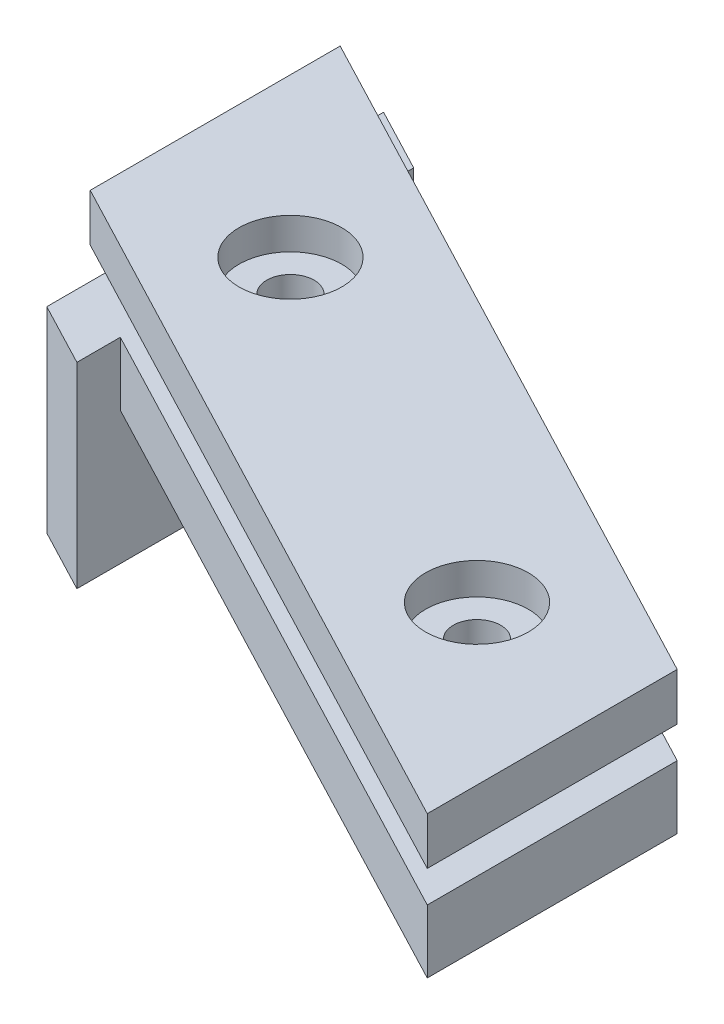
SolidWorks part; units mm, degrees
ref_plane "Front Plane" through (0, 0, 0) normal (0, 0, 1) x (1, 0, 0)
ref_plane "Top Plane" through (0, 0, 0) normal (0, 1, 0) x (1, 0, 0)
ref_plane "Right Plane" through (0, 0, 0) normal (1, 0, 0) x (0, 0, -1)
sketch "Sketch1" plane through (0, 0, 0) normal (0, 1, 0) x (1, 0, 0)
  line L0 (0, 6) -> (0, -19) construction
  line L1 (0, -19) -> (24.7992, -19) construction
  circle A0 centre (0, 0) radius 6
  circle A1 centre (24.7992, -13) radius 6
  dimension "D1" = 28
  dimension "D2" = 12
  dimension "D3" = 12
  dimension "D4" = 25
sketch "Sketch3" plane through (0, 0, 0) normal (0, 1, 0) x (1, 0, 0)
  line L0 (-10, 13.1456) -> (-10, -2.6614)
  line L1 (-10, -2.6614) -> (34.7992, -26.1456)
  line L2 (34.7992, -26.1456) -> (34.7992, -10.3386)
  line L3 (34.7992, -10.3386) -> (-10, 13.1456)
  line L5 (0, 0) -> (24.7992, -13) construction
  line L6 (0, 6) -> (0, -19) construction
  dimension "D1" = 7
  dimension "D2" = 7
  dimension "D3" = 10
  dimension "D4" = 10
extrude "Boss-Extrude1" add sketch "Sketch3" along normal blind 3
extrude "Boss-Extrude3" add sketch "Sketch1" against normal blind 2
sketch "Sketch4" plane through (0, 3, 0) normal (0, 1, 0) x (1, 0, 0)
  circle A0 centre (0, 0) radius 1.5
  circle A1 centre (24.7992, -13) radius 1.5
  dimension "D1" = 3
  dimension "D2" = 3
extrude "Cut-Extrude1" cut sketch "Sketch4" against normal through all
sketch "Sketch5" plane through (0, 3, 0) normal (0, 1, 0) x (1, 0, 0)
  circle A0 centre (0, 0) radius 3.25
  circle A1 centre (24.7992, -13) radius 3.25
  dimension "D1" = 6.5
  dimension "D2" = 6.5
extrude "Cut-Extrude2" cut sketch "Sketch5" against normal blind 2
sketch "Sketch6" plane through (0, -2, 0) normal (0, -1, 0) x (1, 0, 0)
  line L0 (-10, 2.6614) -> (-10, -13.1456)
  line L1 (-10, -13.1456) -> (34.7992, 10.3386)
  line L2 (34.7992, 10.3386) -> (34.7992, 26.1456)
  line L3 (34.7992, 26.1456) -> (-10, 2.6614)
  circle A0 centre (0, 0) radius 1.5
  circle A1 centre (24.7992, 13) radius 1.5
  circle A2 centre (24.7992, 13) radius 1.5 construction
  circle A3 centre (0, 0) radius 1.5 construction
extrude "Boss-Extrude4" add sketch "Sketch6" along normal blind 4 separate body
sketch "Sketch7" plane through (0, -2, 0) normal (0, 1, 0) x (1, 0, 0)
  line L2 (-8, 14.8437) -> (-8, 12.0972) construction
  line L4 (-8, 12.0972) -> (-8, -3.7098) construction
  line L6 (-10, 15.8921) -> (-10, -5.4079)
  line L7 (-10, -5.4079) -> (-6, -7.5047)
  line L8 (-6, -7.5047) -> (-6, 13.7953)
  line L9 (-6, 13.7953) -> (-10, 15.8921)
  line L10 (-10, 13.1456) -> (34.7992, -10.3386) construction
  line L11 (-10, -2.6614) -> (-10, 13.1456) construction
  line L12 (34.7992, -26.1456) -> (-10, -2.6614) construction
  line L13 (-8, -3.7098) -> (-8, -6.4563) construction
  dimension "D1" = 21.3
  dimension "D2" = 4
extrude "Boss-Extrude5" add sketch "Sketch7" against normal blind 12.4
sketch "Sketch9" [suppressed] plane through (0, -14.4, 0) normal (0, -1, 0) x (1, 0, 0)
  line L0 (-6, 5.4079) -> (-21.5, 5.4079)
  line L1 (-6, 7.5047) -> (-6, -13.7953) construction
  line L2 (-21.5, 5.4079) -> (-21.5, 10.4079)
  line L3 (-21.5, 10.4079) -> (-6, 10.4079)
  line L4 (-6, 10.4079) -> (-6, 5.4079)
  line L5 (-10, -15.8921) -> (-21.5, -15.8921)
  line L6 (-21.5, -15.8921) -> (-21.5, -20.8921)
  line L7 (-21.5, -20.8921) -> (-6, -20.8921)
  line L8 (-6, -20.8921) -> (-6, -15.8921)
  line L9 (-6, -13.7953) -> (-10, -15.8921)
  line L10 (-6, -15.8921) -> (-6, -13.7953)
  line L11 (-10, -15.8921) -> (-10, 5.4079) construction
  line L12 (-15.75, 8.9579) -> (-15.75, 10.4079) construction
  line L13 (-15.75, -19.4421) -> (-15.75, -20.8921) construction
  line L14 (-15.75, 7.9579) -> (-15.75, -18.4421) construction
  line L15 (-15.75, -5.2421) -> (-10, -5.2421) construction
  circle A0 centre (-15.75, 7.9579) radius 1
  circle A1 centre (-15.75, -18.4421) radius 1
  point P24 (-15.75, -15.8921)
  dimension "D3" = 2
  dimension "D4" = 26.4
  dimension "D1" = 5
  dimension "D2" = 11.5
extrude "Boss-Extrude6" [suppressed] add sketch "Sketch9" against normal blind 4
sketch "Sketch10" [suppressed] plane through (0, -14.4, 0) normal (0, -1, 0) x (1, 0, 0)
  line L0 (-6, 10.4079) -> (-6, -20.8921)
  line L1 (-6, -20.8921) -> (-10, -20.8921)
  line L2 (-21.5, -20.8921) -> (-6, -20.8921) construction
  line L3 (-10, -20.8921) -> (-10, 10.4079)
  line L4 (-6, 10.4079) -> (-21.5, 10.4079) construction
  line L5 (-10, 10.4079) -> (-6, 10.4079)
  line L6 (-10, -15.8921) -> (-10, 5.4079) construction
extrude "Boss-Extrude7" [suppressed] add sketch "Sketch10" along normal blind 2
sketch "Sketch11" [suppressed] plane through (0, -16.4, 0) normal (0, -1, 0) x (1, 0, 0)
  line L0 (-21.5, 10.4079) -> (-6, 10.4079)
  line L1 (-6, -20.8921) -> (-6, 10.4079) construction
  line L2 (-6, 10.4079) -> (-6, -20.8921)
  line L3 (-6, -20.8921) -> (-21.5, -20.8921)
  line L4 (-21.5, -20.8921) -> (-21.5, -15.8921)
  line L5 (-21.5, -15.8921) -> (-10, -15.8921)
  line L6 (-10, -15.8921) -> (-10, 5.4079)
  line L7 (-10, 5.4079) -> (-21.5, 5.4079)
  line L8 (-21.5, 5.4079) -> (-21.5, 10.4079)
  circle A0 centre (-15.75, -18.4421) radius 1
  circle A1 centre (-15.75, 7.9579) radius 1
  circle A2 centre (-15.75, 7.9579) radius 1 construction
  circle A3 centre (-15.75, -18.4421) radius 1 construction
extrude "Boss-Extrude8" [suppressed] add sketch "Sketch11" along normal blind 3
chamfer "Chamfer2" [suppressed] distance 4 angle 45
chamfer "Chamfer3" [suppressed] distance 3 angle 45
chamfer "Chamfer4" [suppressed] distance 2 distance2 14
